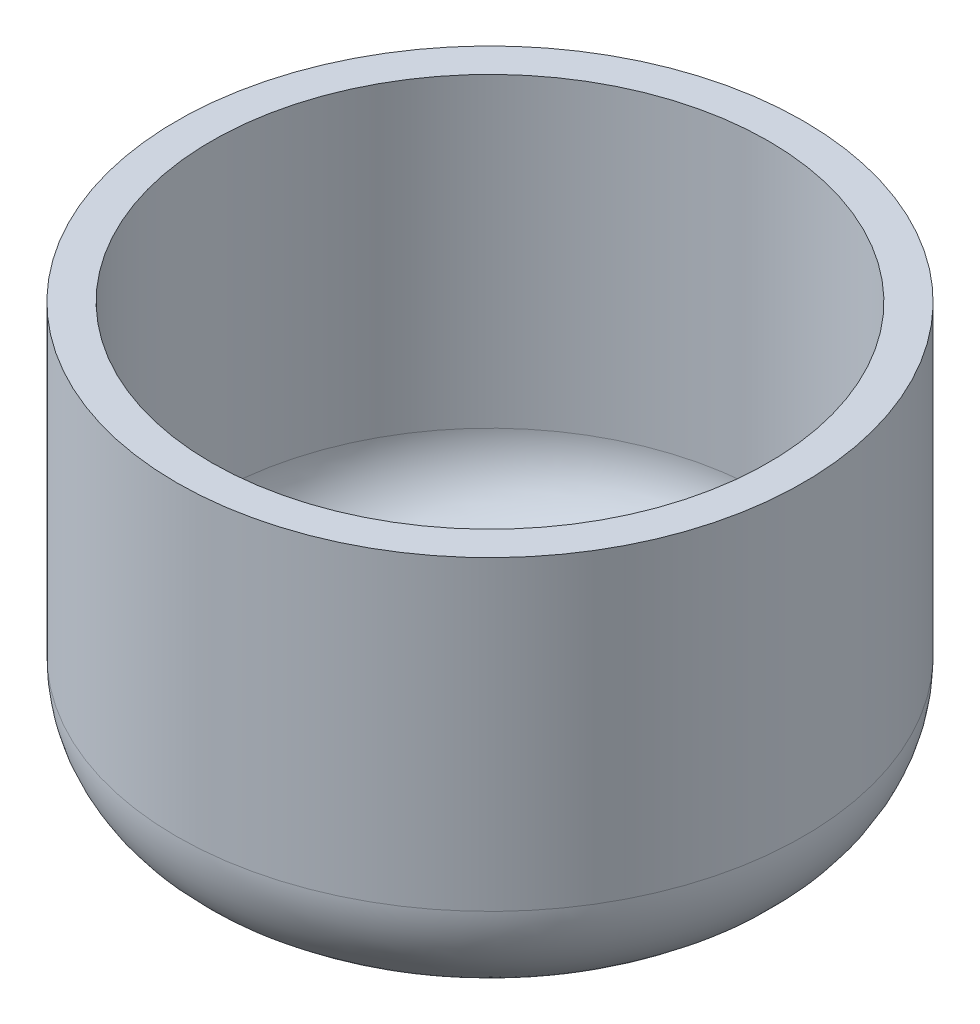
SolidWorks part; units mm, degrees
material "Copper"
ref_plane "Front Plane" through (0, 0, 0) normal (0, 0, 1) x (1, 0, 0)
ref_plane "Top Plane" through (0, 0, 0) normal (0, 1, 0) x (1, 0, 0)
ref_plane "Right Plane" through (0, 0, 0) normal (1, 0, 0) x (0, 0, -1)
sketch "Sketch1" plane through (0, 0, 0) normal (0, 1, 0) x (1, 0, 0)
  circle A0 centre (0, 0) radius 14.2875
  dimension "D1" = 28.575
extrude "Boss-Extrude1" add sketch "Sketch1" along normal blind 19.05
fillet "Fillet1" radius 5.08 1 edges at (0, 0, 14.2875)
shell "Shell1" thickness 1.5875
hole_wizard "#8 Clearance Hole1" positions "Sketch3" profile "Sketch2" hole size "#8" standard "ANSI Inch"
sketch "Sketch3" plane through (0, 1.5875, 0) normal (0, 1, 0) x (1, 0, 0)
  point P0 (0, 0)
sketch "Sketch2" plane through (0, 1.5875, 0) normal (1, 0, 0) x (0, 0, 1)
  line L0 (0, 0) -> (0, 7.7007)
  line L1 (0, 7.7007) -> (2.2479, 6.35)
  line L2 (2.2479, 6.35) -> (2.2479, 0)
  line L5 (2.2479, 0) -> (0, 0)
  line L10 (0, 7.7007) -> (-2.2479, 6.35) construction
  line L11 (0, -6.35) -> (0, 107.95) construction
  dimension "Hole Dia." = 4.4958
  dimension "Hole Depth" = 6.35
  dimension "Drill Angle" = 118
